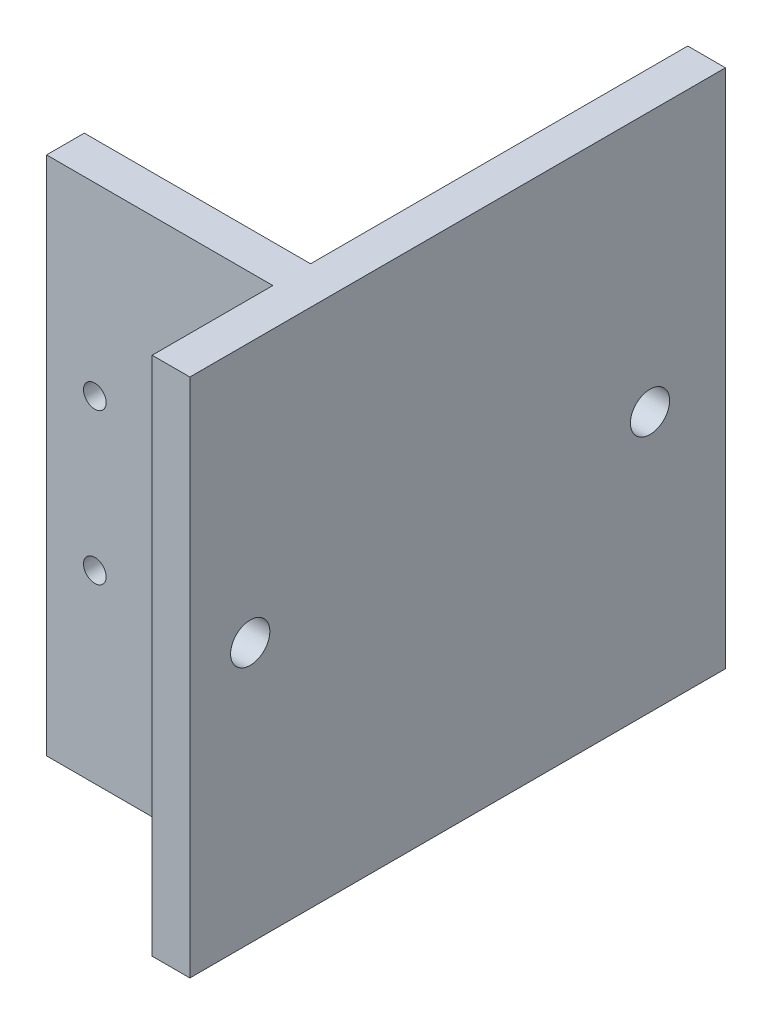
SolidWorks part; units mm, degrees
ref_plane "前视基准面" through (0, 0, 0) normal (0, 0, 1) x (1, 0, 0)
ref_plane "上视基准面" through (0, 0, 0) normal (0, 1, 0) x (1, 0, 0)
ref_plane "右视基准面" through (0, 0, 0) normal (1, 0, 0) x (0, 0, -1)
other "Configuration Table"
sketch "草图1" plane through (0, 0, 0) normal (0, 1, 0) x (1, 0, 0)
  line L0 (30, 0) -> (30, 50)
  line L1 (0, 0) -> (30, 0)
  line L2 (0, 0) -> (0, -5)
  line L3 (0, -5) -> (30, -5)
  line L5 (30, -21) -> (35, -21)
  line L6 (30, -21) -> (30, -5)
  line L7 (30, 50) -> (35, 50)
  line L8 (35, -21) -> (35, 50)
  dimension "D1" = 5
  dimension "D2" = 5
  dimension "D3" = 16
  dimension "D4" = 50
  dimension "D5" = 30
extrude "凸台-拉伸1" add sketch "草图1" along normal blind 69
hole_wizard "孔1" positions "草图2" profile "草图3" legacy end condition through all
sketch "草图2" plane through (0, 0, 5) normal (0, 0, 1) x (1, 0, 0)
  line L0 (30, 69) -> (30, 0) construction
  line L2 (0, 34.5) -> (30, 34.5) construction
  line L3 (0, 69) -> (0, 0) construction
  point P0 (26.4, 44.5)
  point P2 (26.4, 24.5)
  point P4 (6.4, 44.5)
  point P6 (6.4, 24.5)
  dimension "D1" = 3.6
  dimension "D2" = 20
  dimension "D3" = 20
  dimension "D4" = 20
sketch "草图3" plane through (26.4, 44.5, 5) normal (1, 0, 0) x (0, -1, 0)
  line L0 (0, 0) -> (0, 55)
  line L1 (0, 55) -> (1.5, 55)
  line L2 (1.5, 55) -> (1.5, 0)
  line L3 (1.5, 0) -> (0, 0)
  line L4 (0, 110) -> (0, -10) construction
  dimension "直径" = 3
  dimension "深度" = 55
sketch "草图5" plane through (30, 0, 0) normal (-1, 0, 0) x (0, 0, 1)
  line L0 (21, 34.5) -> (5, 34.5) construction
  line L1 (21, 69) -> (21, 0) construction
  line L2 (5, 69) -> (5, 0) construction
  circle A0 centre (13, 34.5) radius 2.6
  dimension "D1" = 5.2
  dimension "D2" = 8
extrude "切除-拉伸1" cut sketch "草图5" against normal blind 10
sketch "草图6" plane through (30, 0, 0) normal (-1, 0, 0) x (0, 0, 1)
  line L0 (0, 34.5) -> (-50, 34.5) construction
  line L1 (0, 69) -> (0, 0) construction
  line L2 (-50, 69) -> (-50, 0) construction
  circle A0 centre (-40, 34.5) radius 2.6
  dimension "D1" = 5.2
  dimension "D2" = 40
extrude "切除-拉伸2" cut sketch "草图6" against normal blind 10
sketch "草图8" plane through (30, 0, 0) normal (-1, 0, 0) x (0, 0, 1)
  line L0 (-50, 69) -> (-50, 0) construction
  line L1 (-51, 29.5) -> (-49, 29.5)
  line L2 (-51, 29.5) -> (-51, 39.5)
  line L3 (-51, 39.5) -> (-49, 39.5)
  line L4 (-49, 29.5) -> (-49, 39.5)
  line L5 (-51, 29.5) -> (-49, 39.5) construction
  line L6 (-51, 39.5) -> (-49, 29.5) construction
  point P0 (-50, 34.5)
  dimension "D1" = 1
  dimension "D2" = 10
extrude "切除-拉伸4" cut sketch "草图8" against normal blind 2
